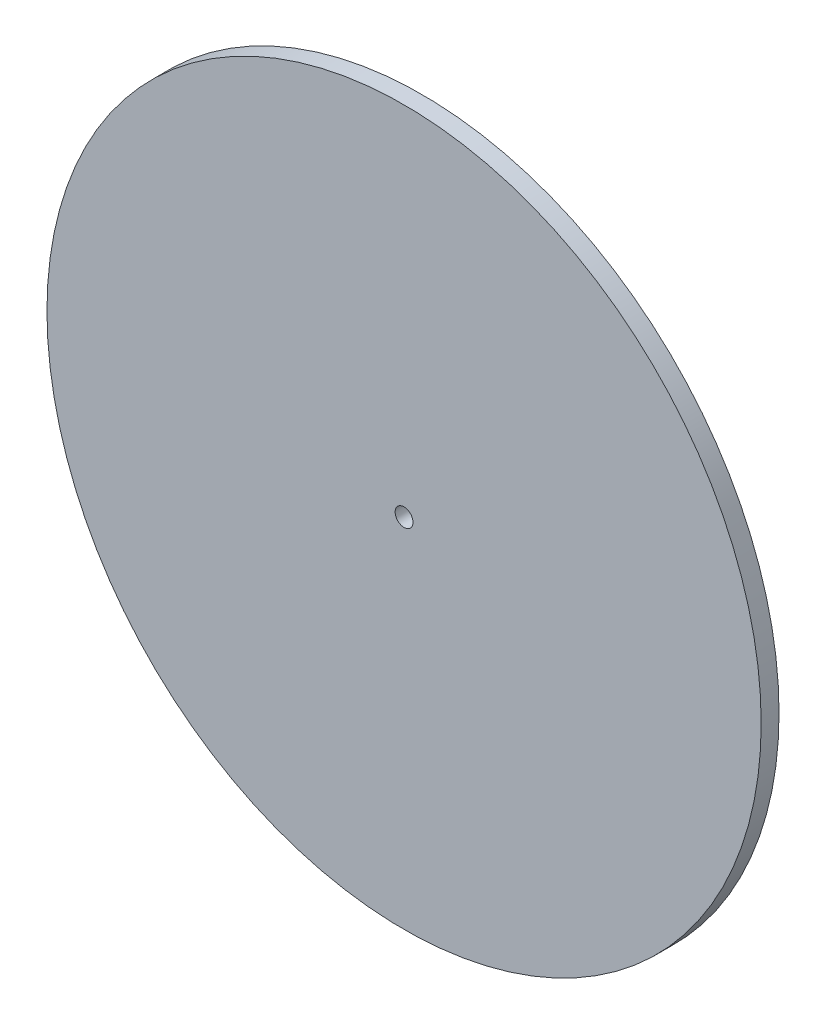
SolidWorks part; units mm, degrees
ref_plane "Front Plane" through (0, 0, 0) normal (0, 0, 1) x (1, 0, 0)
ref_plane "Top Plane" through (0, 0, 0) normal (0, 1, 0) x (1, 0, 0)
ref_plane "Right Plane" through (0, 0, 0) normal (1, 0, 0) x (0, 0, -1)
sketch "Sketch1" plane through (0, 0, 0) normal (0, 0, 1) x (1, 0, 0)
  circle A40 centre (0, 0) radius 100
  circle A41 centre (0, 0) radius 2.5
  dimension "D1" = 200
  dimension "D2" = 5
extrude "Boss-Extrude1" add sketch "Sketch1" against normal blind 5
